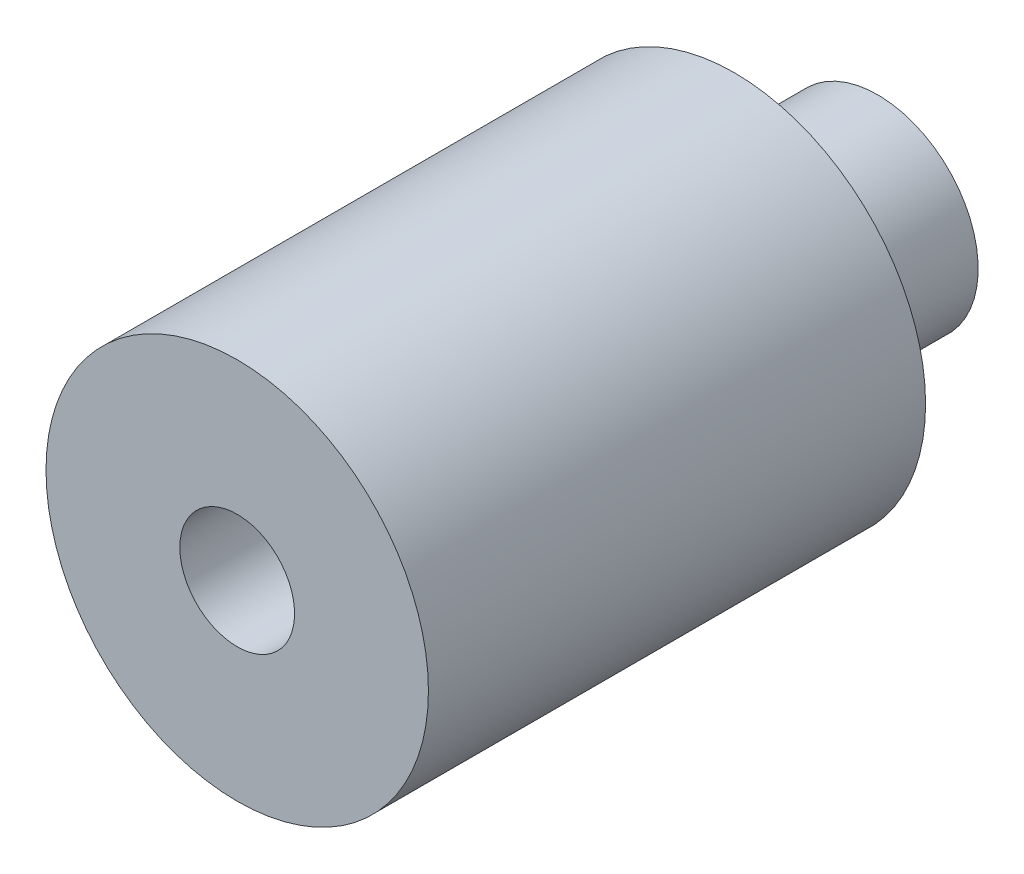
SolidWorks part; units mm, degrees
ref_plane "前视基准面" through (0, 0, 0) normal (0, 0, 1) x (1, 0, 0)
ref_plane "上视基准面" through (0, 0, 0) normal (0, 1, 0) x (1, 0, 0)
ref_plane "右视基准面" through (0, 0, 0) normal (1, 0, 0) x (0, 0, -1)
other "Configuration Table"
sketch "草图1" plane through (0, 0, 0) normal (0, 0, 1) x (1, 0, 0)
  circle A0 centre (0, 0) radius 10
  dimension "D1" = 20
extrude "凸台-拉伸1" add sketch "草图1" along normal blind 26
sketch "草图2" plane through (0, 0, 0) normal (0, 0, -1) x (-1, 0, 0)
  circle A0 centre (0, 0) radius 5.25
  dimension "D1" = 10.5
extrude "凸台-拉伸2" add sketch "草图2" along normal blind 7.5
sketch "草图3" plane through (0, 0, -7.5) normal (0, 0, -1) x (-1, 0, 0)
  circle A0 centre (0, 0) radius 3
  dimension "D1" = 6
extrude "切除-拉伸1" cut sketch "草图3" against normal through all
